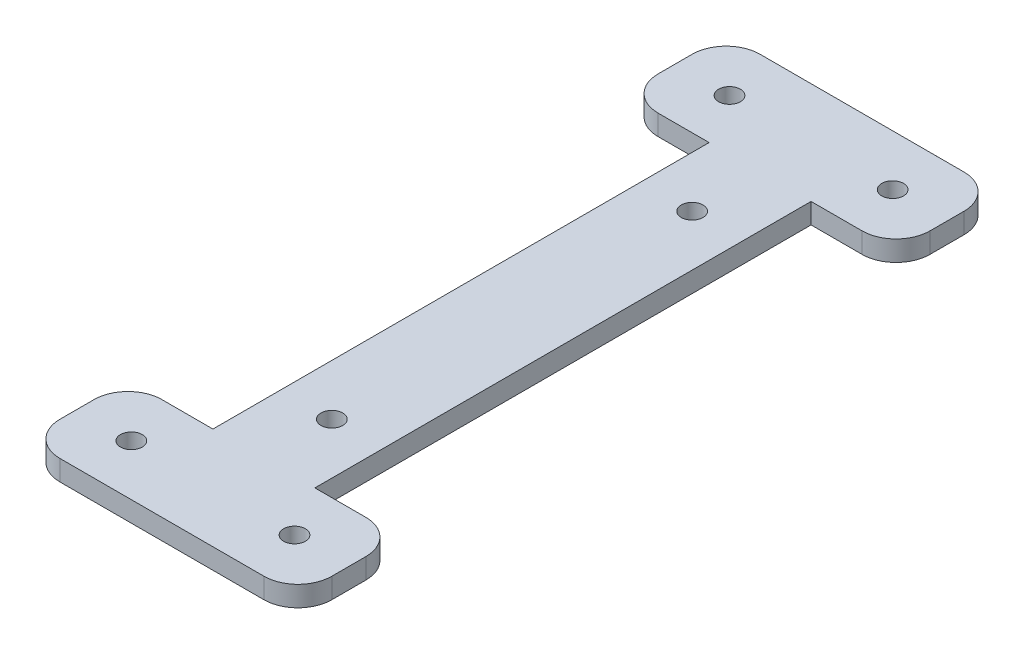
SolidWorks part; units mm, degrees
ref_plane "Front Plane" through (0, 0, 0) normal (0, 0, 1) x (1, 0, 0)
ref_plane "Top Plane" through (0, 0, 0) normal (0, 1, 0) x (1, 0, 0)
ref_plane "Right Plane" through (0, 0, 0) normal (1, 0, 0) x (0, 0, -1)
sketch "Sketch1" plane through (0, 0, 0) normal (0, 1, 0) x (1, 0, 0)
  line L0 (20, 103) -> (20, 0) construction
  line L1 (0, 0) -> (40, 0)
  line L2 (0, 0) -> (0, 15)
  line L3 (0, 15) -> (40, 15)
  line L4 (40, 0) -> (40, 15)
  line L5 (12.5, 15) -> (27.5, 15)
  line L6 (12.5, 15) -> (12.5, 88)
  line L7 (12.5, 88) -> (27.5, 88)
  line L8 (27.5, 15) -> (27.5, 88)
  line L9 (0, 103) -> (40, 103)
  line L10 (0, 103) -> (0, 88)
  line L11 (0, 88) -> (40, 88)
  line L12 (40, 103) -> (40, 88)
  line L13 (0, 95.5) -> (40, 95.5) construction
  line L14 (0, 7.5) -> (40, 7.5) construction
  circle A0 centre (8, 95.5) radius 1.6
  circle A1 centre (8, 7.5) radius 1.6
  circle A2 centre (20, 78) radius 1.6
  circle A3 centre (20, 25) radius 1.6
  circle A4 centre (32, 7.5) radius 1.6
  circle A5 centre (32, 95.5) radius 1.6
  point P15 (20, 88)
  dimension "D4" = 3.2
  dimension "D6" = 10
  dimension "D7" = 10
  dimension "D1" = 15
  dimension "D2" = 73
  dimension "D3" = 40
  dimension "D5" = 8
extrude "Boss-Extrude1" add sketch "Sketch1" along normal blind 3 contours L12 L9 L10 L11 L7 A0 A5 | L3 L8 L7 L6 A3 A2 | L1 L4 L3 L2 A1 A4
fillet "Fillet1" radius 5 8 edges at (40, 1.5, -88) (40, 1.5, -15) (40, 1.5, 0) (0, 1.5, 0) (0, 1.5, -15) (0, 1.5, -88) (0, 1.5, -103) (40, 1.5, -103)
